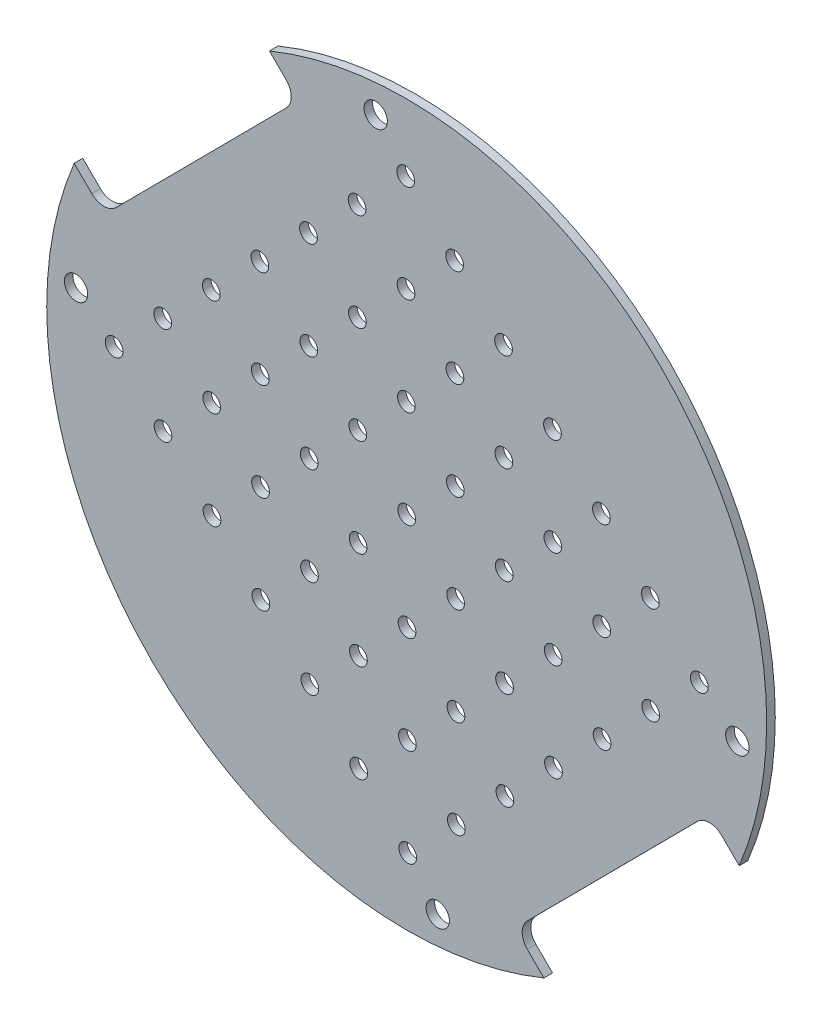
SolidWorks part; units mm, degrees
ref_plane "Front Plane" through (0, 0, 0) normal (0, 0, 1) x (1, 0, 0)
ref_plane "Top Plane" through (0, 0, 0) normal (0, 1, 0) x (1, 0, 0)
ref_plane "Right Plane" through (0, 0, 0) normal (1, 0, 0) x (0, 0, -1)
sketch "Sketch1" plane through (0, 0, 0) normal (0, 0, 1) x (1, 0, 0)
  circle A0 centre (0, 0) radius 66.294
  dimension "D1" = 132.588
extrude "Extrude1" add sketch "Sketch1" along normal blind 1.5875
sketch "Sketch2" plane through (0, 0, 1.5875) normal (0, 0, 1) x (1, 0, 0)
  line L0 (0, 0) -> (0, 66.294) construction
  line L1 (0, 66.294) -> (0, -66.294) construction
  line L2 (0, -66.294) -> (0, 0) construction
  line L3 (0, 0) -> (66.294, 0) construction
  line L4 (66.294, 0) -> (-66.294, 0) construction
  circle A0 centre (0, 0) radius 66.294 construction
sketch "Sketch6" plane through (0, 0, 1.5875) normal (0, 0, 1) x (1, 0, 0)
  line L0 (0, 66.294) -> (0, 51.308) construction
  line L1 (0, 0) -> (0, 66.294) construction
  dimension "D1" = 14.986
sketch "Sketch11" plane through (0, 0, 0) normal (0, 0, -1) x (-1, 0, 0)
  line L0 (-66.294, 0) -> (-55.7449, 0) construction
  line L1 (-55.7449, 0) -> (-55.7449, -19.9509) construction
  line L2 (-55.7449, -19.9509) -> (-68.9299, -33.0443)
  line L3 (-68.9299, -33.0443) -> (-33.1343, -69.0903)
  line L4 (-33.1343, -69.0903) -> (-19.9493, -55.9969)
  line L5 (-19.9493, -55.9969) -> (-55.7449, -19.9509)
  line L6 (0, -66.294) -> (0, -55.7449) construction
  line L7 (0, -55.7449) -> (-19.9493, -55.9969) construction
  circle A0 centre (0, 0) radius 66.294 construction
  dimension "D1" = 50.8
  dimension "D2" = 19.9509
  dimension "D3" = 18.5817
  dimension "D4" = 10.5491
extrude "Extrude3" cut sketch "Sketch11" against normal through all
sketch "Sketch8" plane through (0, 0, 1.5875) normal (0, 0, 1) x (1, 0, 0)
  line L0 (0, 66.294) -> (0, 60.8965) construction
  line L1 (0, 66.294) -> (0, 51.308) construction
  line L2 (0, 60.8965) -> (-5.715, 60.8965) construction
  line L3 (66.294, 0) -> (60.8965, 0) construction
  line L4 (60.8965, 0) -> (60.8965, -5.715) construction
  circle A0 centre (0, 0) radius 66.294 construction
  dimension "D1" = 5.3975
  dimension "D2" = 5.715
pattern_circular "CirPattern4" count 2 over 180 about axis through (0, 0, 0) along (0, 0, 1) of "Extrude3"
hole_wizard "#6 Clearance Hole1" positions "3DSketch3" profile "Sketch10" hole size "#6" standard "Ansi Inch" end condition through all
sketch3d "3DSketch3"
  point P0 (-5.715, 60.8965, 1.5875)
  point P3 (60.8965, -5.715, 1.5875)
sketch "Sketch10" plane through (-5.715, 60.8965, 1.5875) normal (1, 0, 0) x (0, -1, 0)
  line L0 (0, 0) -> (0, 1.5875)
  line L1 (0, 1.5875) -> (2.1526, 1.5875)
  line L2 (2.1526, 1.5875) -> (2.1526, 0)
  line L5 (2.1526, 0) -> (0, 0)
  line L11 (0, -6.35) -> (0, 107.95) construction
  dimension "Thru Hole Dia." = 4.3053
  dimension "Thru Hole Depth" = 1.5875
pattern_circular "CirPattern3" count 2 over 180 about axis through (0, 0, 0) along (0, 0, 1) of "#6 Clearance Hole1"
hole_wizard "#4 Clearance Hole1" positions "Sketch14" profile "Sketch13" hole size "#4" standard "Ansi Inch"
sketch "Sketch14" plane through (0, 0, 1.5875) normal (0, 0, 1) x (1, 0, 0)
  point P1 (0, 0)
sketch "Sketch13" plane through (0, 0, 1.5875) normal (1, 0, 0) x (0, -1, 0)
  line L0 (0, 0) -> (0, 16.2206)
  line L1 (0, 16.2206) -> (1.6319, 15.24)
  line L2 (1.6319, 15.24) -> (1.6319, 0)
  line L5 (1.6319, 0) -> (0, 0)
  line L10 (0, 16.2206) -> (-1.6319, 15.24) construction
  line L11 (0, -6.35) -> (0, 107.95) construction
  dimension "Hole Dia." = 3.2639
  dimension "Hole Depth" = 15.24
  dimension "Drill Angle" = 118
pattern_linear "LPattern1" count 4 spacing 12.7 along (0.7046, 0.7096, 0) count 4 spacing 12.7 along (-0.7046, -0.7096, 0) of "#4 Clearance Hole1"
pattern_linear "LPattern2" count 4 spacing 12.7 along (-0.7096, 0.7046, 0) count 4 spacing 12.7 along (0.7096, -0.7046, 0) of "LPattern1", "#4 Clearance Hole1"
sketch "Sketch15" plane through (0, 0, 1.5875) normal (0, 0, 1) x (1, 0, 0)
  line L0 (-26.8467, -27.0345) -> (-35.7956, -36.046) construction
  line L1 (-19.9493, 55.9969) -> (-55.7449, 19.9509) construction
  line L2 (26.8467, 27.0345) -> (35.7956, 36.046) construction
  dimension "D1" = 12.7
fillet "Fillet1" radius 3.175 4 edges at (-19.9493, 55.9969, 0.7937) (-55.7449, 19.9509, 0.7937) (19.9493, -55.9969, 0.7937) (55.7449, -19.9509, 0.7937)
